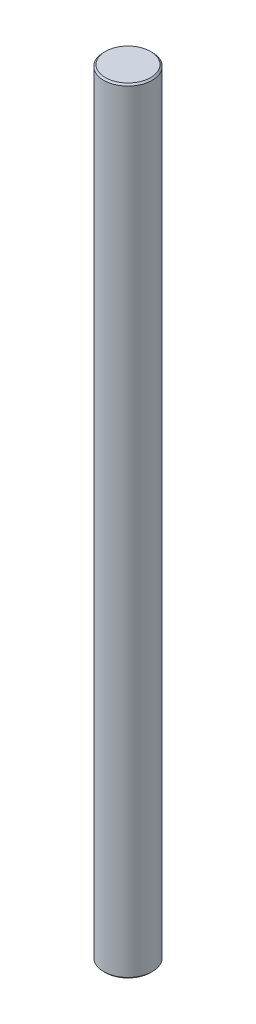
SolidWorks part; units mm, degrees
material "Plain Carbon Steel"
ref_plane "Front Plane" through (0, 0, 0) normal (0, 0, 1) x (1, 0, 0)
ref_plane "Top Plane" through (0, 0, 0) normal (0, 1, 0) x (1, 0, 0)
ref_plane "Right Plane" through (0, 0, 0) normal (1, 0, 0) x (0, 0, -1)
sketch "Sketch1" plane through (0, 0, 0) normal (0, 1, 0) x (1, 0, 0)
  circle A0 centre (0, 0) radius 3.9688
  dimension "D1" = 7.9375
extrude "Boss-Extrude1" add sketch "Sketch1" along normal mid plane 127
chamfer "Chamfer1" distance 0.254 angle 45 2 edges at (0, -63.5, 3.9688) (0, 63.5, 3.9688)
